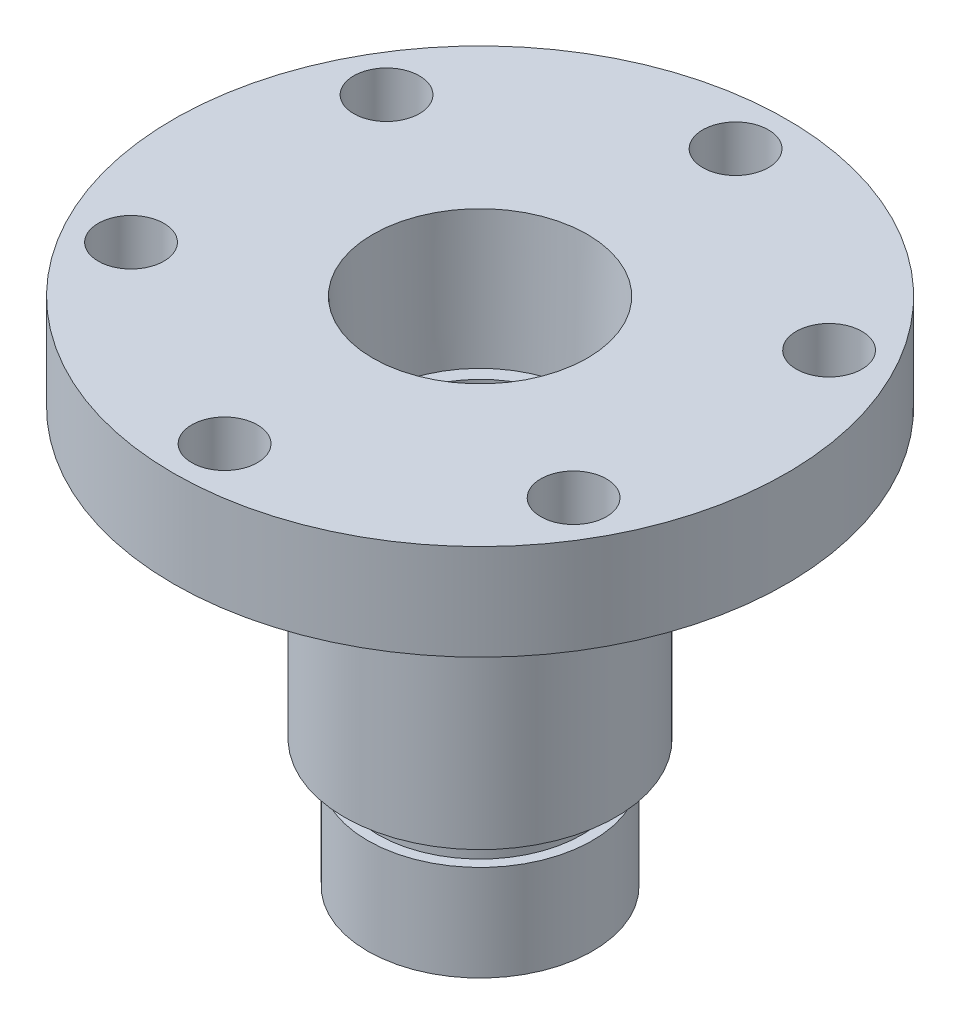
SolidWorks part; units mm, degrees
material "AISI 304"
ref_plane "Front Plane" through (0, 0, 0) normal (0, 0, 1) x (1, 0, 0)
ref_plane "Top Plane" through (0, 0, 0) normal (0, 1, 0) x (1, 0, 0)
ref_plane "Right Plane" through (0, 0, 0) normal (1, 0, 0) x (0, 0, -1)
sketch "Sketch1" plane through (0, 0, 0) normal (0, 0, 1) x (1, 0, 0)
  line L0 (0, 0) -> (0, -60.5188) construction
  line L1 (-7.5, 0) -> (-30.48, 0)
  line L2 (-30.48, 0) -> (-30.48, -9.525)
  line L3 (-30.48, -9.525) -> (-21, -9.525)
  line L4 (-13.5, -9.525) -> (-13.5, -38.1012)
  line L5 (-11.176, -50.8) -> (-7.5, -50.8)
  line L6 (-7.5, -50.8) -> (-7.5, 0)
  line L7 (-13.5, -38.1012) -> (-11, -38.1012)
  line L8 (-11, -38.1012) -> (-11, -39.6887)
  line L9 (-11.176, -41.2762) -> (-10.16, -41.2762)
  line L10 (-10.16, -41.2762) -> (-10.16, -39.6887)
  line L11 (-10.16, -39.6887) -> (-11, -39.6887)
  line L12 (-11.176, -41.2762) -> (-11.176, -50.8)
  line L13 (-18, -9.525) -> (-18, -7.775)
  line L14 (-18, -7.775) -> (-21, -7.775)
  line L15 (-21, -7.775) -> (-21, -9.525)
  line L16 (-18, -9.525) -> (-13.5, -9.525)
  dimension "D1" = 60.96
  dimension "D2" = 27
  dimension "D3" = 9.525
  dimension "D4" = 50.8
  dimension "D5" = 15
  dimension "D6" = 12.7
  dimension "D7" = 22.352
  dimension "D8" = 1.5875
  dimension "D9" = 1.5875
  dimension "D10" = 20.32
  dimension "D11" = 22
  dimension "D12" = 1.75
  dimension "D13" = 36
  dimension "D14" = 42
revolve "Revolve1" add sketch "Sketch1" angle 360 about L0
cosmetic thread "Cosmetic Thread1"
hole_wizard "1/2 NPT Tapped Hole1" positions "Sketch2" profile "Sketch3" size "1/2" standard "ANSI Inch"
sketch "Sketch2" plane through (0, 0, 0) normal (0, 1, 0) x (1, 0, 0)
  point P0 (0, 0)
sketch "Sketch3" plane through (0, 0, 0) normal (1, 0, 0) x (0, 0, 1)
  line L0 (0, 0) -> (0, 27.9705)
  line L1 (8.9281, 22.606) -> (0, 27.9705)
  line L2 (-8.9281, 22.606) -> (0, 27.9705) construction
  line L3 (8.9281, 22.606) -> (8.9281, 13.462)
  line L4 (8.9281, 13.462) -> (10.2617, 13.462)
  line L5 (10.2617, 13.462) -> (10.6647, 0)
  line L6 (-10.2617, 13.462) -> (-10.6647, 0) construction
  line L7 (10.6647, 0) -> (0, 0)
  line L8 (0, -6.35) -> (0, 107.95) construction
  line L11 (-8.9281, 13.462) -> (-10.2617, 13.462) construction
  dimension "Tap Drill Dia." = 17.8562
  dimension "Tap Drill Depth" = 22.606
  dimension "Thread Dia." = 21.3295
  dimension "Thread Angle" = 3.43
  dimension "Thread Depth" = 13.462
  dimension "Drill Angle" = 118
hole_wizard "1/4 Clearance Hole1" positions "Sketch4" profile "Sketch5" hole size "1/4" standard "ANSI Inch"
sketch "Sketch4" plane through (0, 0, 0) normal (0, 1, 0) x (1, 0, 0)
  line L1 (0, 25.4) -> (-21.997, 12.7)
  line L2 (-21.997, 12.7) -> (-21.997, -12.7)
  line L3 (-21.997, -12.7) -> (0, -25.4)
  line L4 (0, -25.4) -> (21.997, -12.7)
  line L5 (21.997, -12.7) -> (21.997, 12.7)
  line L6 (21.997, 12.7) -> (0, 25.4)
  circle A0 centre (0, 0) radius 25.4 construction
  point P3 (0, 25.4)
  point P4 (-21.997, 12.7)
  point P5 (-21.997, -12.7)
  point P6 (0, -25.4)
  point P7 (21.997, -12.7)
  point P8 (21.997, 12.7)
  dimension "D1" = 50.8
sketch "Sketch5" plane through (21.997, 0, -12.7) normal (1, 0, 0) x (0, 0, 1)
  line L0 (0, 0) -> (0, 24.5671)
  line L1 (0, 24.5671) -> (3.2639, 22.606)
  line L2 (3.2639, 22.606) -> (3.2639, 0)
  line L5 (3.2639, 0) -> (0, 0)
  line L10 (0, 24.5671) -> (-3.2639, 22.606) construction
  line L11 (0, -6.35) -> (0, 107.95) construction
  dimension "Hole Dia." = 6.5278
  dimension "Hole Depth" = 22.606
  dimension "Drill Angle" = 118
chamfer "Chamfer1" distance 1 angle 45 1 edges at (0, -9.525, 13.5)
